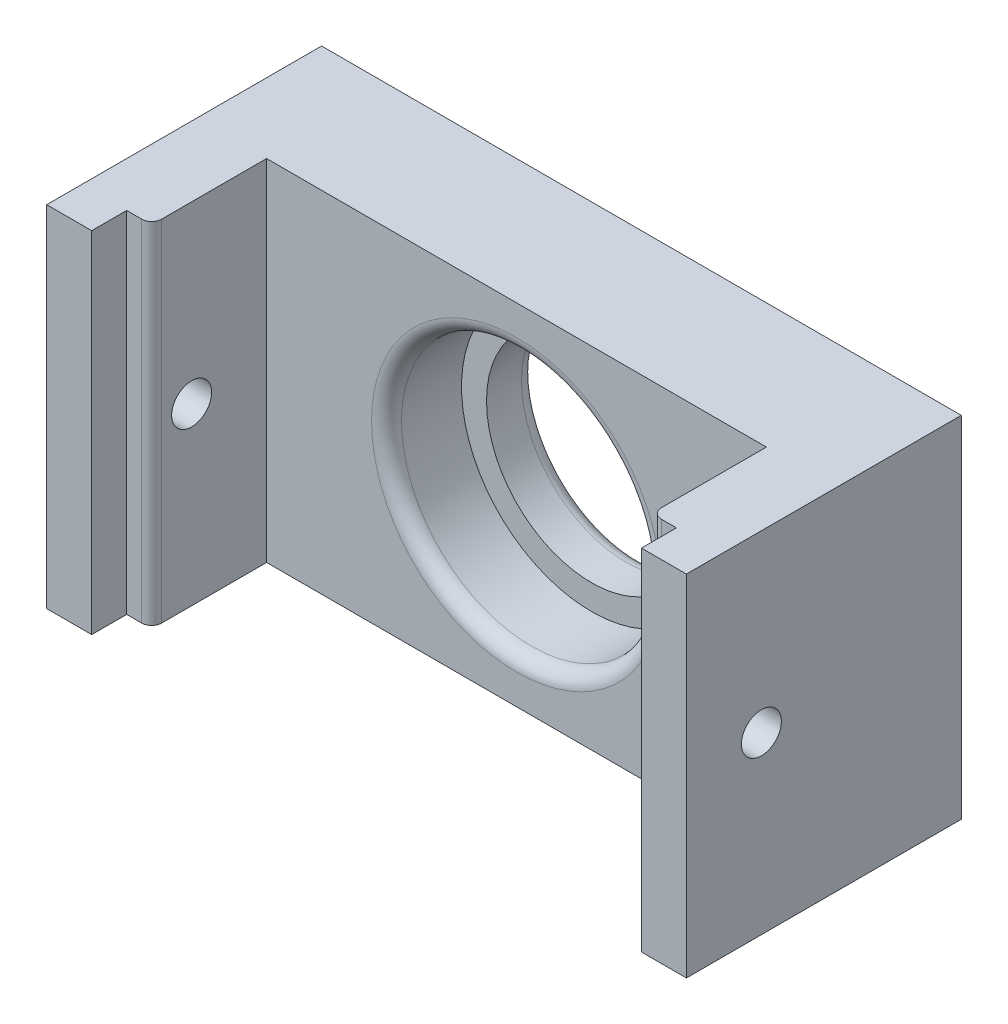
SolidWorks part; units mm, degrees
ref_plane "Front Plane" through (0, 0, 0) normal (0, 0, 1) x (1, 0, 0)
ref_plane "Top Plane" through (0, 0, 0) normal (0, 1, 0) x (1, 0, 0)
ref_plane "Right Plane" through (0, 0, 0) normal (1, 0, 0) x (0, 0, -1)
sketch "Szkic2" plane through (0, 0, 0) normal (0, 0, 1) x (1, 0, 0)
  line L0 (0, 10.5) -> (-32, 10.5)
  line L1 (-32, 10.5) -> (-32, -10.5)
  line L2 (-32, -10.5) -> (0, -10.5)
  line L3 (0, -10.5) -> (32, -10.5)
  line L4 (0, 10.5) -> (32, 10.5)
  line L5 (32, 10.5) -> (32, -10.5)
  line L7 (-32, 10.5) -> (32, 10.5)
  line L8 (-32, 10.5) -> (-32, 17.5)
  line L9 (-32, 17.5) -> (32, 17.5)
  line L10 (32, 10.5) -> (32, 17.5)
  line L11 (-32, -10.5) -> (32, -10.5)
  line L12 (-32, -10.5) -> (-32, -17.5)
  line L13 (-32, -17.5) -> (32, -17.5)
  line L14 (32, -10.5) -> (32, -17.5)
  circle A0 centre (0, 0) radius 10.5
  dimension "D1" = 21
  dimension "D2" = 32
  dimension "D3" = 32
  dimension "D4" = 7
  dimension "D5" = 7
extrude "Dodanie-wyciągnięcie1" add sketch "Szkic2" along normal blind 12.5 contours A0 L0 L1 L2 | A0 L3 L5 L4 | L4 L10 L9 L8 L0 | L14 L3 L2 L12 L13
sketch "Szkic3" plane through (0, 0, 12.5) normal (0, 0, 1) x (1, 0, 0)
  circle A0 centre (0, 0) radius 13
  dimension "D1" = 26
extrude "Wytnij-wyciągnięcie1" cut sketch "Szkic3" against normal blind 7.5
sketch "Szkic4" plane through (0, 0, 12.5) normal (0, 0, 1) x (1, 0, 0)
  line L0 (-32, -17.5) -> (32, -17.5) construction
  line L1 (-32, 17.5) -> (-25, 17.5)
  line L2 (-32, 17.5) -> (-32, -17.5)
  line L3 (-32, -17.5) -> (-25, -17.5)
  line L4 (-25, 17.5) -> (-25, -17.5)
  line L6 (32, 17.5) -> (25, 17.5)
  line L7 (32, 17.5) -> (32, -17.5)
  line L8 (32, -17.5) -> (25, -17.5)
  line L9 (25, 17.5) -> (25, -17.5)
  dimension "D1" = 7
  dimension "D2" = 7
extrude "Dodanie-wyciągnięcie2" add sketch "Szkic4" along normal blind 15
sketch "Szkic6" plane through (25, 0, 0) normal (-1, 0, 0) x (0, 0, 1)
  circle A0 centre (20, 0) radius 2
  dimension "D1" = 4
extrude "Wytnij-wyciągnięcie2" cut sketch "Szkic6" against normal blind 7 contours A0
sketch "Szkic7" plane through (-25, 0, 0) normal (1, 0, 0) x (0, 0, -1)
  circle A0 centre (-20, 0) radius 2
  dimension "D1" = 4
extrude "Wytnij-wyciągnięcie3" cut sketch "Szkic7" against normal blind 7 contours A0
fillet "Zaokrąglenie2" radius 1.5 1 edges at (13, 0, 12.5)
fillet "Zaokrąglenie3" radius 1.5 1 edges at (10.5, 0, 0)
sketch "Szkic8" plane through (0, 0, 27.5) normal (0, 0, 1) x (1, 0, 0)
  line L0 (-32, -17.5) -> (-25, -17.5) construction
  line L1 (-25, 17.5) -> (-27.5, 17.5)
  line L2 (-25, 17.5) -> (-25, -17.5)
  line L3 (-25, -17.5) -> (-27.5, -17.5)
  line L4 (-27.5, 17.5) -> (-27.5, -17.5)
  line L5 (25, -17.5) -> (32, -17.5) construction
  line L6 (25, 17.5) -> (27.5, 17.5)
  line L7 (25, 17.5) -> (25, -17.5)
  line L8 (25, -17.5) -> (27.5, -17.5)
  line L9 (27.5, 17.5) -> (27.5, -17.5)
  dimension "D1" = 2.5
  dimension "D2" = 2.5
extrude "Wytnij-wyciągnięcie4" cut sketch "Szkic8" against normal blind 3.5
fillet "Zaokrąglenie4" radius 1 2 edges at (25, 0, 24) (-25, 0, 24)
